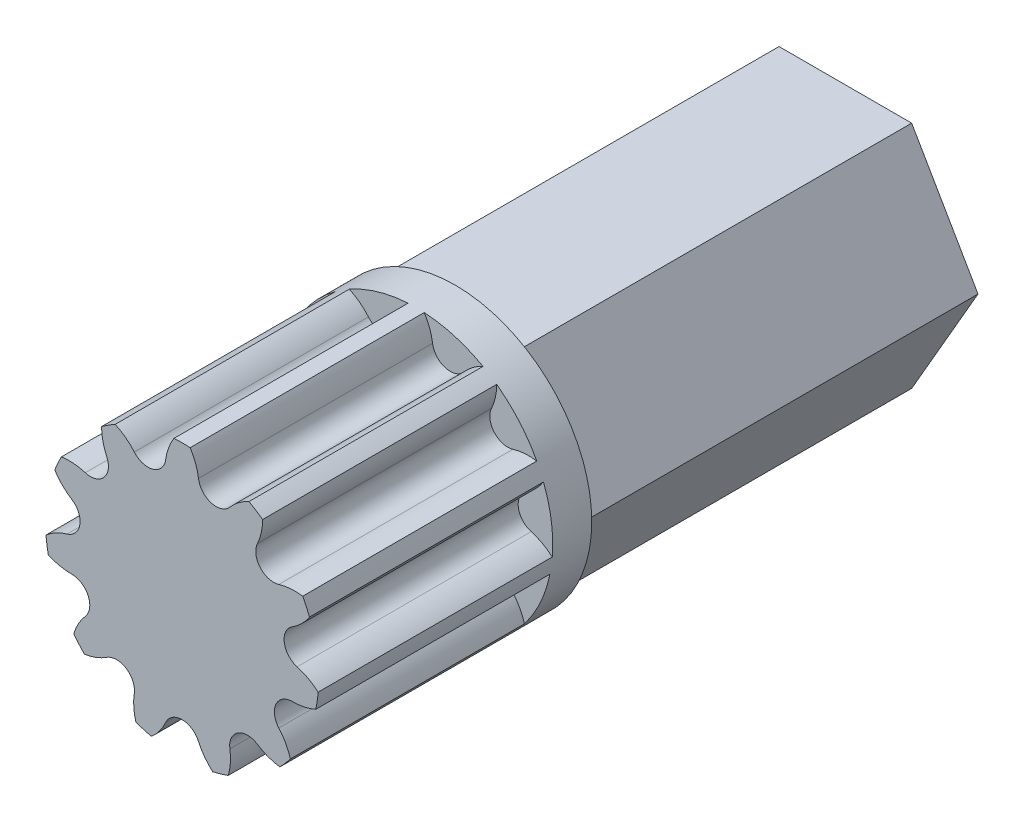
SolidWorks part; units mm, degrees
ref_plane "Front Plane" through (0, 0, 0) normal (0, 0, 1) x (1, 0, 0)
ref_plane "Top Plane" through (0, 0, 0) normal (0, 1, 0) x (1, 0, 0)
ref_plane "Right Plane" through (0, 0, 0) normal (1, 0, 0) x (0, 0, -1)
sketch "Sketch1" plane through (0, 0, 0) normal (0, 0, 1) x (1, 0, 0)
  line L0 (3.4, 0) -> (1.7, 2.9445)
  line L1 (1.7, 2.9445) -> (-1.7, 2.9445)
  line L2 (-1.7, 2.9445) -> (-3.4, 0)
  line L3 (-3.4, 0) -> (-1.7, -2.9445)
  line L4 (-1.7, -2.9445) -> (1.7, -2.9445)
  line L5 (1.7, -2.9445) -> (3.4, 0)
  circle A0 centre (0, 0) radius 3.4 construction
extrude "Boss-Extrude1" add sketch "Sketch1" along normal blind 10 contours L0 L1 L2 L3 L4 L5
sketch "Sketch2" plane through (0, 0, 10) normal (0, 0, 1) x (1, 0, 0)
  circle A0 centre (0, 0) radius 3.5
  dimension "D1" = 7
extrude "Boss-Extrude2" add sketch "Sketch2" along normal blind 7
sketch "Sketch5" plane through (0, 0, 17) normal (0, 0, 1) x (1, 0, 0)
  circle A0 centre (0, 0) radius 1.55 construction
  circle A1 centre (0, 0) radius 3.5 construction
  arc A2 (-1.225, -2.6808) -> (-1.2205, -2.6359) centre (-1.6786, -2.6119) ccw
  arc A3 (-0.3984, -2.8773) -> (-0.4188, -2.9175) centre (0, -3.1048) ccw
  arc A4 (0.3984, -2.8773) -> (-0.3984, -2.8773) centre (0, -3.1048) ccw
  arc A5 (0.4188, -2.9175) -> (0.3984, -2.8773) centre (0, -3.1048) ccw
  arc A6 (1.2205, -2.6359) -> (1.225, -2.6808) centre (1.6786, -2.6119) ccw
  arc A7 (1.9296, -2.228) -> (1.8907, -2.2052) centre (1.6786, -2.6119) ccw
  arc A8 (2.8279, -0.8311) -> (2.7828, -0.8329) centre (2.8242, -1.2898) ccw
  arc A9 (2.4518, -1.5576) -> (2.4799, -1.5929) centre (2.8242, -1.2898) ccw
  arc A10 (2.9047, 0.0152) -> (2.9474, 0.0007) centre (3.0732, 0.4419) ccw
  arc A11 (2.8283, 0.8297) -> (2.7913, 0.8038) centre (3.0732, 0.4419) ccw
  arc A12 (2.8279, -0.8311) -> (3.4296, -0.7022) centre (2.8391, 0.586) ccw
  arc A13 (2.7828, -0.8329) -> (2.4518, -1.5576) centre (2.8242, -1.2898) ccw
  arc A14 (2.7766, -2.1321) -> (2.4799, -1.5929) centre (1.4164, -2.5294) ccw
  arc A15 (2.5055, -2.4449) -> (2.7766, -2.1321) centre (0, 0) ccw
  arc A16 (1.9296, -2.228) -> (2.5055, -2.4449) centre (2.7052, -1.042) ccw
  arc A17 (1.8907, -2.2052) -> (1.2205, -2.6359) centre (1.6786, -2.6119) ccw
  arc A18 (1.1831, -3.2948) -> (1.225, -2.6808) centre (-0.176, -2.8936) ccw
  arc A19 (0.786, -3.4114) -> (1.1831, -3.2948) centre (0, 0) ccw
  arc A20 (0.4188, -2.9175) -> (0.786, -3.4114) centre (1.7124, -2.3391) ccw
  arc A21 (-0.786, -3.4114) -> (-0.4188, -2.9175) centre (-1.7124, -2.3391) ccw
  arc A22 (-1.1831, -3.2948) -> (-0.786, -3.4114) centre (0, 0) ccw
  arc A23 (-1.225, -2.6808) -> (-1.1831, -3.2948) centre (0.176, -2.8936) ccw
  arc A24 (3.4296, -0.7022) -> (3.4885, -0.2925) centre (0, 0) ccw
  arc A25 (3.4885, -0.2925) -> (2.9474, 0.0007) centre (2.559, -1.3621) ccw
  arc A26 (2.7913, 0.8038) -> (2.9047, 0.0152) centre (3.0732, 0.4419) ccw
  arc A27 (2.8283, 0.8297) -> (3.2648, 1.2634) centre (2.0716, 2.0279) ccw
  arc A28 (3.2648, 1.2634) -> (3.0928, 1.64) centre (0, 0) ccw
  arc A29 (-1.8907, -2.2052) -> (-1.9296, -2.228) centre (-1.6786, -2.6119) ccw
  arc A30 (-2.4799, -1.5929) -> (-2.4518, -1.5576) centre (-2.8242, -1.2898) ccw
  arc A31 (-2.7828, -0.8329) -> (-2.8279, -0.8311) centre (-2.8242, -1.2898) ccw
  arc A32 (-2.9474, 0.0007) -> (-2.9047, 0.0152) centre (-3.0732, 0.4419) ccw
  arc A33 (-2.7913, 0.8038) -> (-2.8283, 0.8297) centre (-3.0732, 0.4419) ccw
  arc A34 (-1.2205, -2.6359) -> (-1.8907, -2.2052) centre (-1.6786, -2.6119) ccw
  arc A35 (-2.5055, -2.4449) -> (-1.9296, -2.228) centre (-2.7052, -1.042) ccw
  arc A36 (-2.7766, -2.1321) -> (-2.5055, -2.4449) centre (0, 0) ccw
  arc A37 (-2.4799, -1.5929) -> (-2.7766, -2.1321) centre (-1.4164, -2.5294) ccw
  arc A38 (-2.4518, -1.5576) -> (-2.7828, -0.8329) centre (-2.8242, -1.2898) ccw
  arc A39 (-3.4296, -0.7022) -> (-2.8279, -0.8311) centre (-2.8391, 0.586) ccw
  arc A40 (-3.4885, -0.2925) -> (-3.4296, -0.7022) centre (0, 0) ccw
  arc A41 (-2.9474, 0.0007) -> (-3.4885, -0.2925) centre (-2.559, -1.3621) ccw
  arc A42 (-2.9047, 0.0152) -> (-2.7913, 0.8038) centre (-3.0732, 0.4419) ccw
  arc A43 (-3.2648, 1.2634) -> (-2.8283, 0.8297) centre (-2.0716, 2.0279) ccw
  arc A44 (-2.4792, 1.5941) -> (-2.4354, 1.5832) centre (-2.3464, 2.0332) ccw
  arc A45 (-1.9137, 2.1853) -> (-1.9307, 2.2271) centre (-2.3464, 2.0332) ccw
  arc A46 (-1.2238, 2.6814) -> (-1.1929, 2.6485) centre (-0.8747, 2.979) ccw
  arc A47 (-0.4284, 2.873) -> (-0.4202, 2.9173) centre (-0.8747, 2.979) ccw
  arc A48 (2.4354, 1.5832) -> (2.4792, 1.5941) centre (2.3464, 2.0332) ccw
  arc A49 (1.9307, 2.2271) -> (1.9137, 2.1853) centre (2.3464, 2.0332) ccw
  arc A50 (3.0928, 1.64) -> (2.4792, 1.5941) centre (2.8892, 0.2376) ccw
  arc A51 (1.9137, 2.1853) -> (2.4354, 1.5832) centre (2.3464, 2.0332) ccw
  arc A52 (1.9307, 2.2271) -> (2.0635, 2.828) centre (0.6464, 2.826) ccw
  arc A53 (2.0635, 2.828) -> (1.7152, 3.0518) centre (0, 0) ccw
  arc A54 (1.1929, 2.6485) -> (1.2238, 2.6814) centre (0.8747, 2.979) ccw
  arc A55 (0.4202, 2.9173) -> (0.4284, 2.873) centre (0.8747, 2.979) ccw
  arc A56 (1.7152, 3.0518) -> (1.2238, 2.6814) centre (2.3021, 1.7619) ccw
  arc A57 (0.4284, 2.873) -> (1.1929, 2.6485) centre (0.8747, 2.979) ccw
  arc A58 (0.4202, 2.9173) -> (0.207, 3.4946) centre (-0.984, 2.7268) ccw
  arc A59 (0.207, 3.4946) -> (0, 3.5008) centre (0, 0) ccw
  arc A60 (0, 3.5008) -> (-0.207, 3.4946) centre (0, 0) ccw
  arc A61 (-0.207, 3.4946) -> (-0.4202, 2.9173) centre (0.984, 2.7268) ccw
  arc A62 (-1.1929, 2.6485) -> (-0.4284, 2.873) centre (-0.8747, 2.979) ccw
  arc A63 (-1.2238, 2.6814) -> (-1.7152, 3.0518) centre (-2.3021, 1.7619) ccw
  arc A64 (-1.7152, 3.0518) -> (-2.0635, 2.828) centre (0, 0) ccw
  arc A65 (-2.0635, 2.828) -> (-1.9307, 2.2271) centre (-0.6464, 2.826) ccw
  arc A66 (-2.4354, 1.5832) -> (-1.9137, 2.1853) centre (-2.3464, 2.0332) ccw
  arc A67 (-2.4792, 1.5941) -> (-3.0928, 1.64) centre (-2.8892, 0.2376) ccw
  arc A68 (-3.0928, 1.64) -> (-3.2648, 1.2634) centre (0, 0) ccw
  circle A69 centre (0, 0) radius 3.5008
  point P105 (0, 0)
  point P107 (0, 0)
extrude "Cut-Extrude1" cut sketch "Sketch5" against normal blind 6 flip side to cut contours A42 A33 A43 A68 A67 A44 A66 A45 A65 A64 A63 A46 A62 A47 A61 A60 A59 A58 A55 A57 A54 A56 A53 A52 A49 A51 A48 A50 A28 A27 A11 A26 A10 A25 A24 A12 A8 A13 A9 A14 A15 A16 A7 A17 A6 A18 A19 A20 A5 A4 A3 A21 A22 A23 A2 A34 A29 A35 A36 A37 A30 A38 A31 A39 A40 A41 A32
